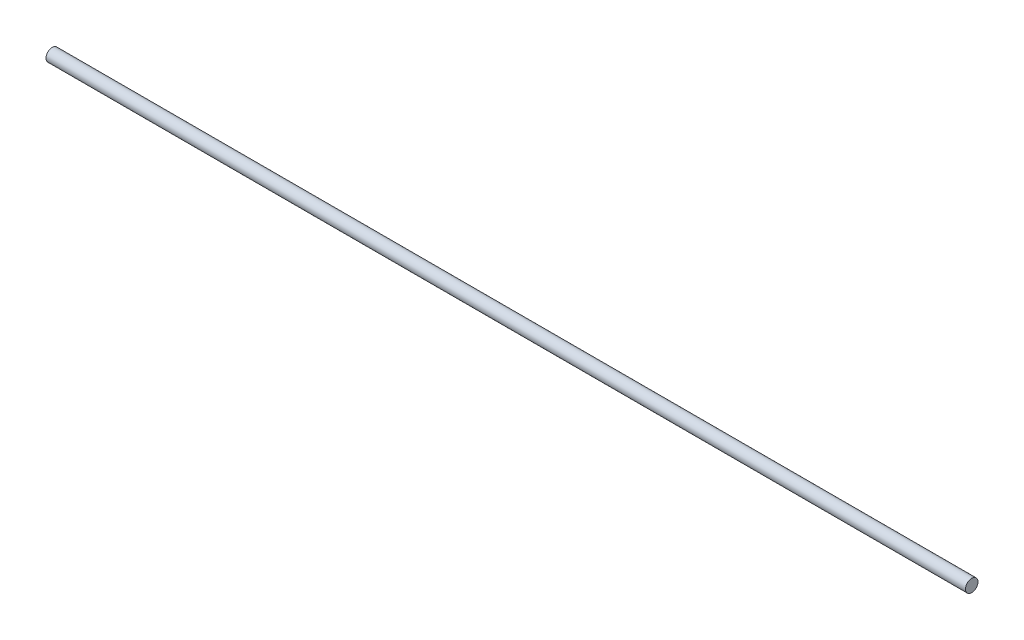
SolidWorks part; units mm, degrees
material "Plain Carbon Steel"
ref_plane "Front Plane" through (0, 0, 0) normal (0, 0, 1) x (1, 0, 0)
ref_plane "Top Plane" through (0, 0, 0) normal (0, 1, 0) x (1, 0, 0)
ref_plane "Right Plane" through (0, 0, 0) normal (1, 0, 0) x (0, 0, -1)
sketch "Sketch1" plane through (0, 0, 0) normal (1, 0, 0) x (0, 0, -1)
  circle A0 centre (0, 0) radius 1.9844
  dimension "D1" = 3.9688
extrude "Boss-Extrude1" add sketch "Sketch1" along normal mid plane 292.1
